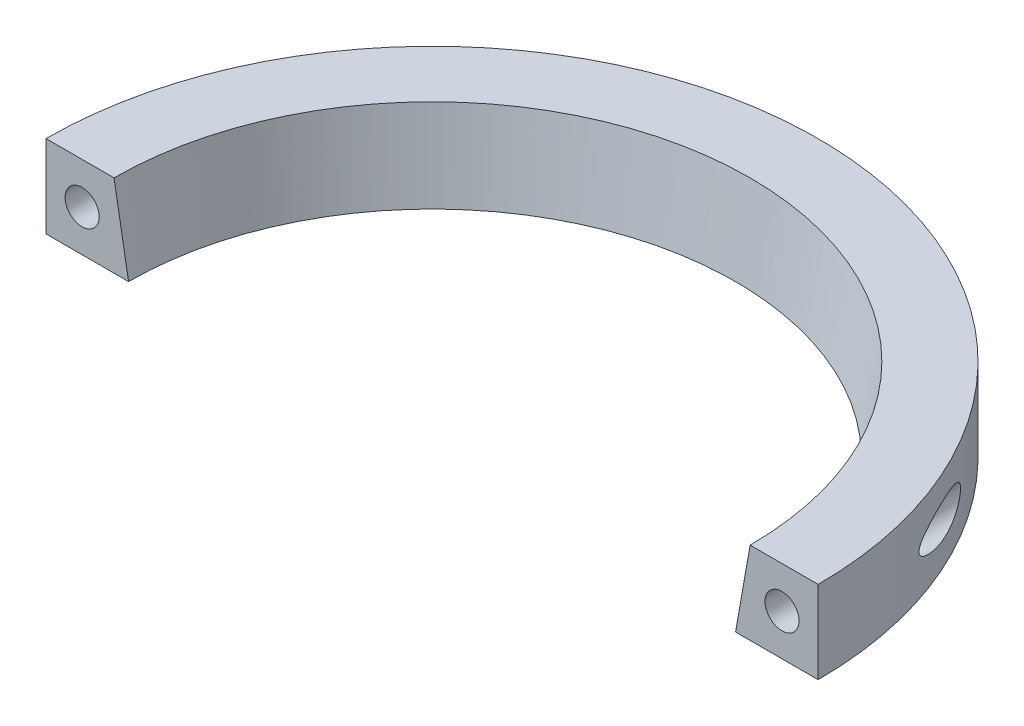
SolidWorks part; units mm, degrees
ref_plane "Front Plane" through (0, 0, 0) normal (0, 0, 1) x (1, 0, 0)
ref_plane "Top Plane" through (0, 0, 0) normal (0, 1, 0) x (1, 0, 0)
ref_plane "Right Plane" through (0, 0, 0) normal (1, 0, 0) x (0, 0, -1)
sketch "Sketch1" plane through (0, 0, 0) normal (0, 1, 0) x (1, 0, 0)
  circle A0 centre (0, 0) radius 16.205
  dimension "D1" = 32.41
ref_plane "Plane1" through (0, 8.21, 0) normal (0, 1, 0) x (1, 0, 0)
sketch "Sketch2" plane through (0, 8.21, 0) normal (0, 1, 0) x (1, 0, 0)
  circle A0 centre (0, 0) radius 19.665
  dimension "D1" = 39.33
sketch "Sketch3" plane through (0, 0, 0) normal (0, 0, 1) x (1, 0, 0)
  line L2 (16.205, 0) -> (-16.205, 0) construction
  line L3 (19.665, 8.21) -> (-19.665, 8.21) construction
  line L4 (-30.8106, 8.21) -> (-37.4, 8.21)
  line L5 (-37.4, 8.21) -> (-37.4, 0.21)
  line L6 (-37.4, 0.21) -> (-29.4, 0.21)
  line L7 (0, 0) -> (0, 8.21) construction
  line L8 (-30.8106, 8.21) -> (-29.4, 0.21)
  line L9 (-29.4, 0.21) -> (-29.4, 11.5872) construction
  dimension "D1" = 8
  dimension "D2" = 37.4
  dimension "D3" = 8
  dimension "D4" = 10
revolve "Revolve1" add sketch "Sketch3" angle 360 about L7
ref_plane "Plane2" through (0, 0, -37.4) normal (0, 0, -1) x (-1, 0, 0)
sketch "Sketch5" plane through (0, 0, 0) normal (0, 1, 0) x (1, 0, 0)
  line L1 (-37.4, 0) -> (107.8722, 0)
  line L2 (-37.4, 0) -> (-37.4, -50.4431)
  line L3 (-37.4, -50.4431) -> (107.8722, -50.4431)
  line L4 (107.8722, 0) -> (107.8722, -50.4431)
  circle A0 centre (0, 0) radius 37.4 construction
extrude "Cut-Extrude3" cut sketch "Sketch5" against normal through all and the other way through all
sketch "Sketch4" plane through (0, 0, 0) normal (0, 0, -1) x (-1, 0, 0)
  line L0 (37.4, 4.21) -> (33.9, 4.21) construction
  line L2 (37.4, 0.21) -> (37.4, 8.21) construction
  line L3 (0, 0) -> (0, 20.1991) construction
  line L4 (-37.4, 4.21) -> (-33.9, 4.21) construction
  circle A2 centre (33.9, 4.21) radius 2.5 construction
  circle A4 centre (-33.9, 4.21) radius 2.5 construction
  point P12 (33.9, 4.21)
  point P16 (-33.9, 4.21)
  point P17 (33.9, 4.21)
  point P18 (-33.9, 4.21)
  dimension "D1" = 5
  dimension "D2" = 3.5
hole_wizard "M4x0.7 Tapped Hole2" positions "Sketch13" profile "Sketch14" tap size "M4x0.7" standard "ANSI Metric" end condition up to next
sketch "Sketch13" plane through (0, 0, 0) normal (0, 0, 1) x (1, 0, 0)
  point P0 (-33.9, 4.21)
  point P3 (33.9, 4.21)
cosmetic thread "Hole Thread9" parameters "D2"=4
cosmetic thread "Hole Thread10" parameters "D2"=4
sketch "Sketch14" plane through (-33.9, 4.21, 0) normal (1, 0, 0) x (0, -1, 0)
  line L0 (0, 0) -> (0, 15.7972)
  line L1 (0, 15.7972) -> (1.65, 15.7972)
  line L2 (1.65, 15.7972) -> (1.65, 0)
  line L5 (1.65, 0) -> (0, 0)
  line L11 (0, -6.35) -> (0, 107.95) construction
  dimension "Thru Tap Drill Dia." = 3.3
  dimension "Thru Tap Drill Depth" = 15.7972
